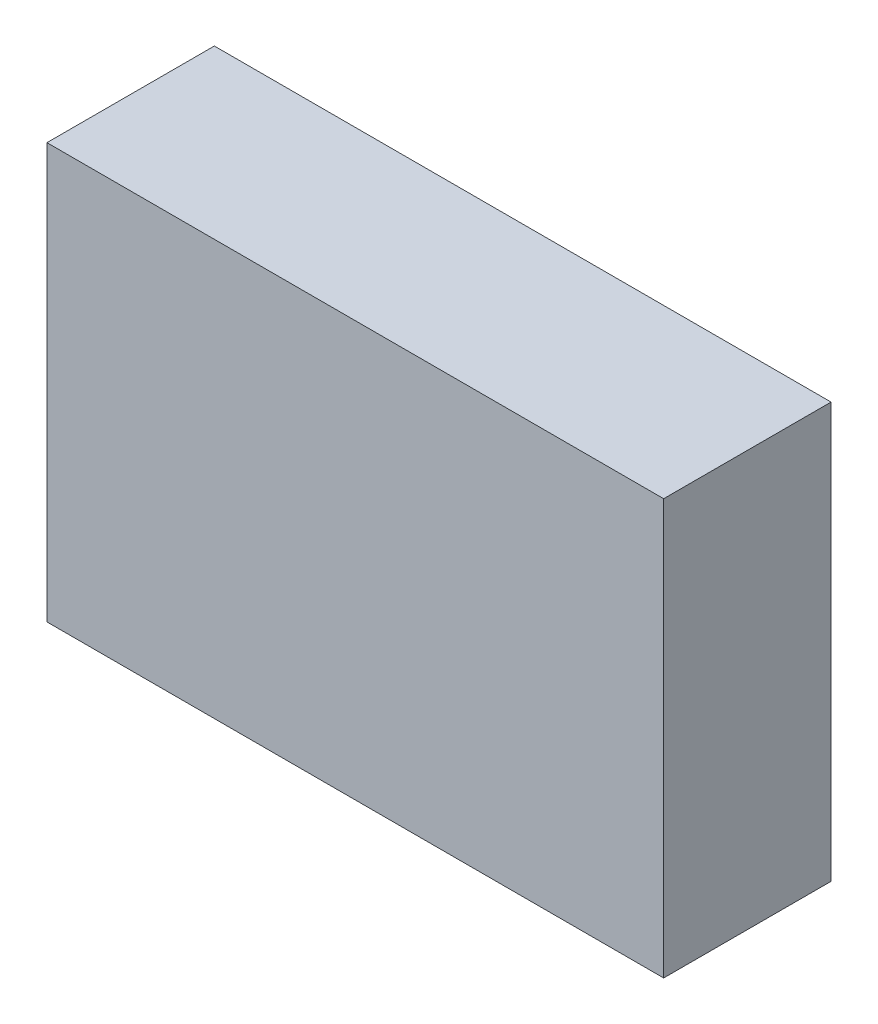
SolidWorks part; units mm, degrees
ref_plane "前视基准面" through (0, 0, 0) normal (0, 0, 1) x (1, 0, 0)
ref_plane "上视基准面" through (0, 0, 0) normal (0, 1, 0) x (1, 0, 0)
ref_plane "右视基准面" through (0, 0, 0) normal (1, 0, 0) x (0, 0, -1)
sketch "草图1" plane through (0, 0, 0) normal (0, 0, 1) x (1, 0, 0)
  line L5 (0, 0) -> (67.2, 0)
  line L6 (0, 0) -> (0, -45.23)
  line L7 (0, -45.23) -> (67.2, -45.23)
  line L8 (67.2, 0) -> (67.2, -45.23)
  dimension "D1" = 67.2
  dimension "D2" = 45.23
extrude "凸台-拉伸1" add sketch "草图1" along normal blind 18.24
